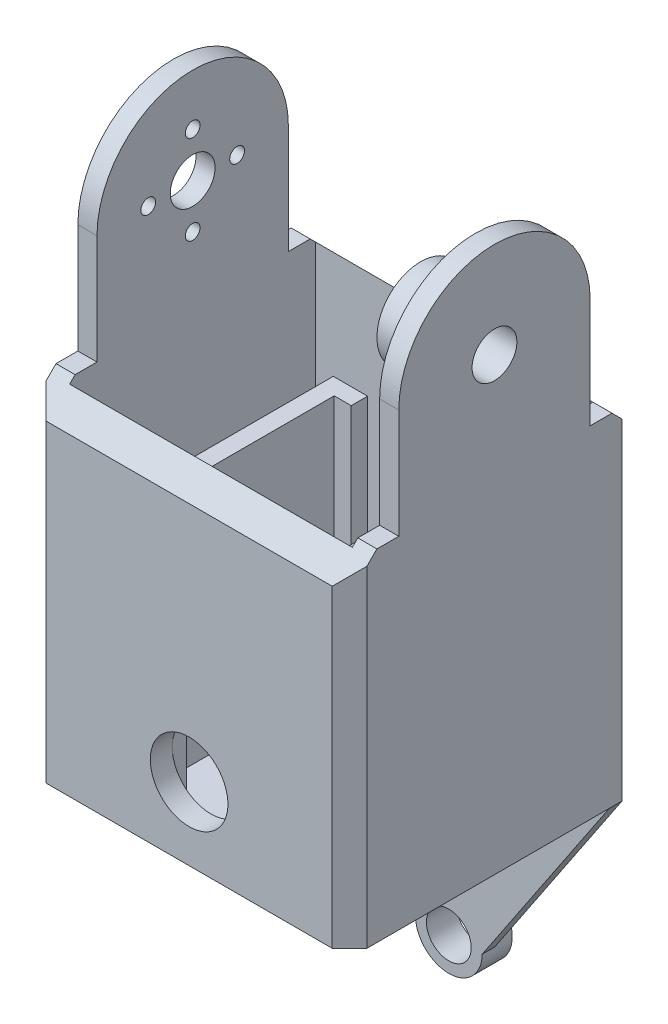
SolidWorks part; units mm, degrees
material "PLA"
ref_plane "Front Plane" through (0, 0, 0) normal (0, 0, 1) x (1, 0, 0)
ref_plane "Top Plane" through (0, 0, 0) normal (0, 1, 0) x (1, 0, 0)
ref_plane "Right Plane" through (0, 0, 0) normal (1, 0, 0) x (0, 0, -1)
sketch "Sketch1" plane through (0, 0, 0) normal (1, 0, 0) x (0, 0, -1)
  line L0 (-17.5, 0) -> (-17.5, -20)
  line L1 (17.5, 0) -> (17.5, -20)
  line L2 (17.5, -20) -> (22.5, -20)
  line L3 (-17.5, -20) -> (-22.5, -20)
  line L4 (22.5, -20) -> (22.5, -76)
  line L5 (-22.5, -20) -> (-22.5, -76)
  line L6 (22.5, -76) -> (-22.5, -76)
  arc A0 (17.5, 0) -> (-17.5, 0) centre (0, 0) ccw
  circle A1 centre (0, 0) radius 4.1
  dimension "D1" = 35
  dimension "D7" = 8.2
  dimension "D2" = 20
  dimension "D3" = 5
  dimension "D4" = 5
  dimension "D5" = 56
  dimension "D6" = 56
extrude "Boss-Extrude1" add sketch "Sketch1" against normal blind 3.5
sketch "Sketch2" plane through (0, 0, 0) normal (1, 0, 0) x (0, 0, -1)
  line L7 (-17.5, 0) -> (-17.5, -20)
  line L8 (-17.5, -20) -> (-22.5, -20)
  line L9 (-22.5, -20) -> (-22.5, -76)
  line L10 (-22.5, -76) -> (22.5, -76)
  line L11 (22.5, -76) -> (22.5, -20)
  line L12 (22.5, -20) -> (17.5, -20)
  line L13 (17.5, -20) -> (17.5, 0)
  line L16 (-22.5, -20) -> (-22.5, -76)
  line L17 (-22.5, -76) -> (22.5, -76)
  line L18 (22.5, -76) -> (22.5, -20)
  line L28 (-22.5, -20) -> (-26.5, -20)
  line L29 (-26.5, -20) -> (-26.5, -79.175)
  line L30 (22.5, -20) -> (26.5, -20)
  line L31 (26.5, -20) -> (26.5, -79.175)
  line L45 (-26.5, -79.175) -> (26.5, -79.175)
  arc A1 (17.5, 0) -> (-17.5, 0) centre (0, 0) ccw
  dimension "D2" = 4
  dimension "D3" = 4
  dimension "D1" = 0
extrude "Boss-Extrude2" add sketch "Sketch2" along normal blind 51.7 and the other way blind 3.5
chamfer "Chamfer2" distance 5 angle 45 2 edges at (24.1, -20, -26.5) (24.1, -20, 26.5)
sketch "Sketch4" plane through (0, -76, 0) normal (0, 1, 0) x (1, 0, 0)
  line L1 (0, 22.5) -> (51.7, 22.5)
  line L2 (0, 22.5) -> (0, -22.5)
  line L3 (0, -22.5) -> (51.7, -22.5)
  line L4 (51.7, 22.5) -> (51.7, -22.5)
extrude "Cut-Extrude1" cut sketch "Sketch4" against normal up to next
sketch "Sketch5" plane through (51.7, 0, 0) normal (1, 0, 0) x (0, 0, -1)
  line L9 (21.5, -20) -> (17.5, -20)
  line L10 (26.5, -25) -> (21.5, -20)
  line L11 (26.5, -79.175) -> (26.5, -25)
  line L12 (-26.5, -79.175) -> (26.5, -79.175)
  line L13 (-26.5, -25) -> (-26.5, -79.175)
  line L14 (-21.5, -20) -> (-26.5, -25)
  line L15 (-17.5, -20) -> (-21.5, -20)
  line L16 (-17.5, 0) -> (-17.5, -20)
  line L17 (17.5, -20) -> (17.5, 0)
  line L18 (21.5, -20) -> (17.5, -20)
  line L19 (26.5, -25) -> (21.5, -20)
  line L20 (26.5, -79.175) -> (26.5, -25)
  line L21 (-26.5, -79.175) -> (26.5, -79.175)
  line L22 (-26.5, -25) -> (-26.5, -79.175)
  line L23 (-21.5, -20) -> (-26.5, -25)
  line L24 (-17.5, -20) -> (-21.5, -20)
  line L25 (-17.5, 0) -> (-17.5, -20)
  line L26 (17.5, -20) -> (17.5, 0)
  arc A1 (17.5, 0) -> (-17.5, 0) centre (0, 0) ccw
  arc A2 (17.5, 0) -> (-17.5, 0) centre (0, 0) ccw
  circle A4 centre (0, 0) radius 4.1
  dimension "D2" = 8.2
  dimension "D1" = 0
extrude "Boss-Extrude3" add sketch "Sketch5" along normal blind 3.5
sketch "Sketch9" plane through (55.2, 0, 0) normal (1, 0, 0) x (0, 0, -1)
  circle A0 centre (0, 0) radius 8.125 construction
  circle A1 centre (0, 8.125) radius 1.35
  circle A2 centre (8.125, 0) radius 1.35
  circle A3 centre (0, -8.125) radius 1.35
  circle A4 centre (-8.125, 0) radius 1.35
  dimension "D1" = 16.25
  dimension "D2" = 2.7
  dimension "D3" = 2.7
  dimension "D4" = 2.7
  dimension "D5" = 2.7
extrude "Cut-Extrude3" cut sketch "Sketch9" against normal up to next
sketch "Sketch10" plane through (0, -79.175, 0) normal (0, -1, 0) x (1, 0, 0)
  line L2 (0, 22.5) -> (51.7, 22.5)
  line L9 (0, 22.5) -> (0, -22.5)
  line L10 (0, -22.5) -> (51.7, -22.5)
  line L11 (51.7, 22.5) -> (51.7, -22.5)
extrude "Boss-Extrude5" add sketch "Sketch10" along normal blind 3.175
sketch "Sketch26" plane through (0, 0, 26.5) normal (0, 0, 1) x (1, 0, 0)
  line L0 (25.85, -82.35) -> (25.85, -69.065) construction
  line L1 (55.2, -82.35) -> (-3.5, -82.35) construction
  circle A0 centre (25.85, -69.065) radius 7.1
  dimension "D1" = 14.2
extrude "Cut-Extrude6" cut sketch "Sketch26" against normal blind 4
sketch "Sketch27" plane through (0, -79.175, 0) normal (0, 1, 0) x (1, 0, 0)
  line L0 (13.4899, 12.1001) -> (13.4937, -19.3) construction
  line L1 (38.2062, -19.3) -> (38.2062, 12.1001) construction
  line L2 (25.85, -22.5) -> (25.85, 20.6118) construction
  line L3 (0, -22.5) -> (51.7, -22.5) construction
  line L4 (38.4062, -22.5) -> (38.4062, 12.1001)
  line L5 (13.2938, -22.5) -> (13.2938, 12.1001)
  line L6 (13.2938, 12.1001) -> (10.1188, 12.1001)
  line L7 (10.1188, 12.1001) -> (10.1188, -22.5)
  line L8 (10.1188, -22.5) -> (13.2938, -22.5)
  line L9 (38.4062, 12.1001) -> (41.5812, 12.1001)
  line L10 (41.5812, 12.1001) -> (41.5812, -22.5)
  line L11 (41.5812, -22.5) -> (38.4062, -22.5)
  dimension "D1" = 0.2
  dimension "D2" = 3.175
  dimension "D3" = 3.175
extrude "Boss-Extrude6" add sketch "Sketch27" along normal up to surface (45.22 mm away)
sketch "Sketch29" plane through (0, 0, -26.5) normal (0, 0, -1) x (-1, 0, 0)
  line L0 (-25.85, -82.35) -> (-25.85, -117.07) construction
  line L1 (3.5, -82.35) -> (-55.2, -82.35) construction
  line L2 (-55.2, -82.35) -> (-31.95, -117.07)
  line L3 (-19.75, -117.07) -> (3.5, -82.35)
  line L4 (-30.85, -103.5033) -> (-40.9973, -88.35)
  line L5 (3.5, -82.35) -> (-55.2, -82.35) construction
  line L6 (-20.85, -103.5033) -> (-10.7027, -88.35)
  line L7 (-40.9973, -88.35) -> (-40.9973, -82.35)
  line L8 (-10.7027, -88.35) -> (-10.7027, -82.35)
  line L9 (-30.85, -103.5033) -> (-20.85, -103.5033)
  circle A0 centre (-25.85, -117.07) radius 4.1
  circle A1 centre (-25.85, -117.07) radius 6.1
  dimension "D2" = 8.2
  dimension "D3" = 12.2
  dimension "D1" = 34.72
  dimension "D4" = 6
  dimension "D5" = 6
  dimension "D6" = 10
extrude "Boss-Extrude8" add sketch "Sketch29" against normal blind 5.5
chamfer "Chamfer3" distance 3.175 angle 45 6 edges at (55.2, -53.675, -26.5) (-3.5, -53.675, -26.5) (55.2, -53.675, 26.5) (-3.5, -53.675, 26.5) (43.575, -99.71, -26.5) (8.125, -99.71, -26.5)
sketch "Sketch30" plane through (0, 0, 0) normal (1, 0, 0) x (0, 0, -1)
  circle A0 centre (0, 0) radius 4.1
  circle A1 centre (0, 0) radius 8
  dimension "D1" = 8.2
  dimension "D2" = 16
extrude "Boss-Extrude9" add sketch "Sketch30" along normal blind 10
sketch "Sketch31" plane through (0, -20, 0) normal (0, 1, 0) x (1, 0, 0)
  line L0 (5, 8) -> (5, -8) construction
  line L1 (10, 8) -> (0, 8) construction
  line L2 (0, -8) -> (10, -8) construction
  circle A0 centre (5, 0) radius 0.95
  dimension "D1" = 1.9
extrude "Cut-Extrude7" cut sketch "Sketch31" along normal through all
sketch "Sketch32" plane through (0, -79.175, 0) normal (0, 1, 0) x (1, 0, 0)
  line L0 (13.7903, 12.4) -> (13.7903, 12.6) construction
  line L1 (15.4899, 12.4) -> (13.79, 12.4) construction
  line L2 (13.7903, 12.6) -> (16.4, 12.6) construction
  line L3 (16.6, 12.4) -> (16.6, 12.4787) construction
  line L4 (16.4, 12.6) -> (13.2938, 12.6)
  line L5 (13.2938, 12.1001) -> (13.2938, 12.6)
  line L6 (10.1188, 12.1001) -> (10.1188, 15.6001)
  line L7 (16.4, 12.6) -> (16.4, 15.6001)
  line L8 (16.4, 15.6001) -> (10.1188, 15.6001)
  line L9 (10.1188, 12.1001) -> (13.2938, 12.1001)
  line M12 (10.1188, 12.1001) -> (13.2938, 12.1001)
  dimension "D1" = 0.2
  dimension "D2" = 0.2
  dimension "D3" = 3.5
extrude "Boss-Extrude10" add sketch "Sketch32" along normal up to surface (45.22 mm away) contours L7 L8 L6 L5 L4 M12 up to face at (11.7063, -33.955, 5.1999)
sketch "Sketch33" plane through (0, -79.175, 0) normal (0, 1, 0) x (1, 0, 0)
  line L0 (13.1937, -19.6) -> (18.8801, -19.6) construction
  line L1 (13.2938, -22.5) -> (18.6801, -22.5)
  line L2 (13.2938, -22.5) -> (13.2938, -19.8)
  line L3 (13.2938, -19.8) -> (18.6801, -19.8)
  line L4 (18.6801, -22.5) -> (18.6801, -19.8)
  line L5 (13.7937, -19.6) -> (14.9937, -19.6) construction
  line L6 (18.85, -19.6) -> (19.084, -19.6) construction
  line L7 (18.8801, -19.6) -> (18.8801, -21.0143) construction
  dimension "D1" = 0.2
  dimension "D2" = 0.2
extrude "Boss-Extrude11" add sketch "Sketch33" along normal up to surface (45.22 mm away) up to face at (13.2709, -33.955, -1.9001)
ref_plane "Plane1" through (25.85, 0, 0) normal (-1, 0, 0) x (0, 0, 1)
mirror "Mirror1" about plane through (25.85, 0, 0) normal (-1, 0, 0) of "Boss-Extrude11", "Boss-Extrude10"
sketch "Sketch34" plane through (0, -33.955, 0) normal (0, 1, 0) x (1, 0, 0)
  line L0 (13.2938, -19.8) -> (13.2938, 12.6) construction
  line L1 (13.2938, 12.6) -> (16.4, 12.6) construction
  line L2 (16.4, 12.6) -> (16.4, 15.6001) construction
  line L3 (16.4, 15.6001) -> (10.1188, 15.6001) construction
  line L4 (10.1188, 15.6001) -> (10.1188, -22.5) construction
  line L5 (10.1188, -22.5) -> (18.6801, -22.5) construction
  line L6 (18.6801, -22.5) -> (18.6801, -19.8) construction
  line L7 (18.6801, -19.8) -> (13.2938, -19.8) construction
  line L8 (41.5812, -22.5) -> (41.5812, 15.6001) construction
  line L9 (41.5812, 15.6001) -> (35.3, 15.6001) construction
  line L10 (35.3, 15.6001) -> (35.3, 12.6) construction
  line L11 (35.3, 12.6) -> (38.4062, 12.6) construction
  line L12 (38.4062, 12.6) -> (38.4062, -19.8) construction
  line L13 (38.4062, -19.8) -> (33.0199, -19.8) construction
  line L14 (33.0199, -19.8) -> (33.0199, -22.5) construction
  line L15 (33.0199, -22.5) -> (41.5812, -22.5) construction
  line L16 (13.2938, -19.8) -> (13.2938, 12.6)
  line L17 (13.2938, 12.6) -> (16.4, 12.6)
  line L18 (16.4, 12.6) -> (16.4, 15.6001)
  line L19 (16.4, 15.6001) -> (10.1188, 15.6001)
  line L20 (10.1188, 15.6001) -> (10.1188, -22.5)
  line L21 (10.1188, -22.5) -> (18.6801, -22.5)
  line L22 (18.6801, -22.5) -> (18.6801, -19.8)
  line L23 (18.6801, -19.8) -> (13.2938, -19.8)
  line L24 (41.5812, -22.5) -> (41.5812, 15.6001)
  line L25 (41.5812, 15.6001) -> (35.3, 15.6001)
  line L26 (35.3, 15.6001) -> (35.3, 12.6)
  line L27 (35.3, 12.6) -> (38.4062, 12.6)
  line L28 (38.4062, 12.6) -> (38.4062, -19.8)
  line L29 (38.4062, -19.8) -> (33.0199, -19.8)
  line L30 (33.0199, -19.8) -> (33.0199, -22.5)
  line L31 (33.0199, -22.5) -> (41.5812, -22.5)
extrude "Boss-Extrude12" add sketch "Sketch34" along normal blind 0.2
ref_plane "Plane2" through (-13.5, 0, 0) normal (-1, 0, 0) x (0, 0, 1)
mirror "Mirror3" about plane through (-13.5, 0, 0) normal (-1, 0, 0) of bodies 131
delete or keep bodies "Body-Delete/Keep 1" type delete bodies bodies 131
